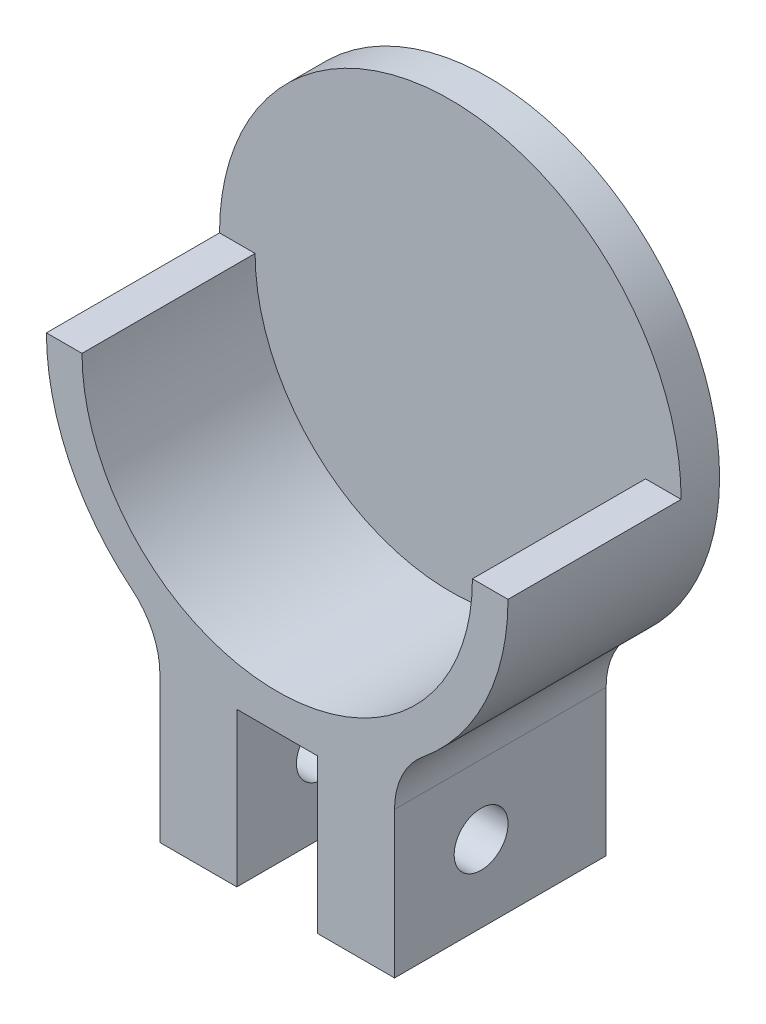
SolidWorks part; units mm, degrees
ref_plane "前视基准面" through (0, 0, 0) normal (0, 0, 1) x (1, 0, 0)
ref_plane "上视基准面" through (0, 0, 0) normal (0, 1, 0) x (1, 0, 0)
ref_plane "右视基准面" through (0, 0, 0) normal (1, 0, 0) x (0, 0, -1)
sketch "草图1" plane through (0, 0, 0) normal (0, 0, 1) x (1, 0, 0)
  line L3 (-6.1, -20) -> (-2.1, -20)
  line L4 (-2.1, -20) -> (-2.1, -12)
  line L5 (0, -1000) -> (0, 49000) construction
  line L9 (-2.1, -12) -> (2.1, -12)
  line L10 (-6.1, -20) -> (-6.1, -10.3339)
  line L11 (-12, 0) -> (-10.15, 0)
  line L12 (10.15, 0) -> (12, 0)
  line L13 (6.1, -20) -> (6.1, -10.3339)
  line L14 (2.1, -20) -> (2.1, -12)
  line L15 (6.1, -20) -> (2.1, -20)
  arc A0 (-10.15, 0) -> (10.15, 0) centre (0, 0) ccw
  arc A3 (-12, 0) -> (-6.1, -10.3339) centre (0, 0) ccw
  arc A4 (6.1, -10.3339) -> (12, 0) centre (0, 0) ccw
  point P4 (-6.1, -10.3339)
  point P16 (-10.15, 0)
  point P17 (10.1476, -0.2211)
  point P18 (10.15, 0)
  dimension "D1" = 20.3
  dimension "D2" = 4
  dimension "D6" = 12
  dimension "D3" = 24
  dimension "D4" = 2.1
  dimension "D5" = 8
extrude "凸台-拉伸1" add sketch "草图1" along normal blind 9
sketch "草图3" plane through (-6.1, 0, 0) normal (-1, 0, 0) x (0, 0, 1)
  line L0 (4.5, -1000) -> (4.5, 49000) construction
  line L3 (9, -20) -> (0, -20) construction
  circle A0 centre (4.5, -16) radius 1.4
  point P5 (4.5, -20)
  dimension "D1" = 2.8
  dimension "D2" = 4
extrude "切除-拉伸1" cut sketch "草图3" against normal through all
fillet "圆角1" radius 4 2 edges at (6.1, -10.3339, 4.5) (-6.1, -10.3339, 4.5)
sketch "草图4" plane through (0, 0, 0) normal (0, 0, -1) x (-1, 0, 0)
  line L9 (-2.1, -12) -> (2.1, -12)
  line L10 (2.1, -12) -> (2.1, -20)
  line L11 (2.1, -20) -> (6.1, -20)
  line L12 (6.1, -20) -> (6.1, -12.4093)
  line L13 (12, 0) -> (10.15, 0)
  line L14 (-10.15, 0) -> (-12, 0)
  line L15 (-6.1, -12.4093) -> (-6.1, -20)
  line L16 (-6.1, -20) -> (-2.1, -20)
  line L17 (-2.1, -20) -> (-2.1, -12)
  line L18 (-2.1, -12) -> (2.1, -12)
  line L19 (2.1, -12) -> (2.1, -20)
  line L20 (2.1, -20) -> (6.1, -20)
  line L21 (6.1, -20) -> (6.1, -12.4093)
  line L24 (-6.1, -12.4093) -> (-6.1, -20)
  line L25 (-6.1, -20) -> (-2.1, -20)
  line L26 (-2.1, -20) -> (-2.1, -12)
  arc A0 (7.575, -9.307) -> (-7.575, -9.307) centre (0, 0) ccw
  arc A5 (7.575, -9.307) -> (6.1, -12.4093) centre (10.1, -12.4093) ccw
  arc A6 (7.575, -9.307) -> (12, 0) centre (0, 0) ccw
  arc A7 (-10.15, 0) -> (10.15, 0) centre (0, 0) ccw
  arc A8 (-12, 0) -> (-7.575, -9.307) centre (0, 0) ccw
  arc A9 (-6.1, -12.4093) -> (-7.575, -9.307) centre (-10.1, -12.4093) ccw
  arc A10 (7.575, -9.307) -> (6.1, -12.4093) centre (10.1, -12.4093) ccw
  arc A11 (7.575, -9.307) -> (12, 0) centre (0, 0) ccw
  arc A13 (-12, 0) -> (-7.575, -9.307) centre (0, 0) ccw
  arc A14 (-6.1, -12.4093) -> (-7.575, -9.307) centre (-10.1, -12.4093) ccw
  line M15 (-2.1, -12) -> (2.1, -12)
  line M16 (2.1, -12) -> (2.1, -20)
  line M17 (2.1, -20) -> (6.1, -20)
  line M18 (6.1, -20) -> (6.1, -12.4093)
  arc M19 (6.1, -12.4093) -> (7.575, -9.307) centre (10.1, -12.4093) cw
  arc M20 (7.575, -9.307) -> (12, 0) centre (0, 0) ccw
  line M21 (12, 0) -> (10.15, 0)
  arc M22 (10.15, 0) -> (-10.15, 0) centre (0, 0) cw
  line M23 (-10.15, 0) -> (-12, 0)
  arc M24 (-12, 0) -> (-7.575, -9.307) centre (0, 0) ccw
  arc M25 (-7.575, -9.307) -> (-6.1, -12.4093) centre (-10.1, -12.4093) cw
  line M26 (-6.1, -12.4093) -> (-6.1, -20)
  line M27 (-6.1, -20) -> (-2.1, -20)
  line M28 (-2.1, -20) -> (-2.1, -12)
  dimension "D2" = 24
  dimension "D1" = 0
extrude "凸台-拉伸2" add sketch "草图4" along normal blind 2 contours A0 M21 M23 M22 | M28 M15 M16 M17 M18 M19 M20 M21 M22 M23 M24 M25 M26 M27
